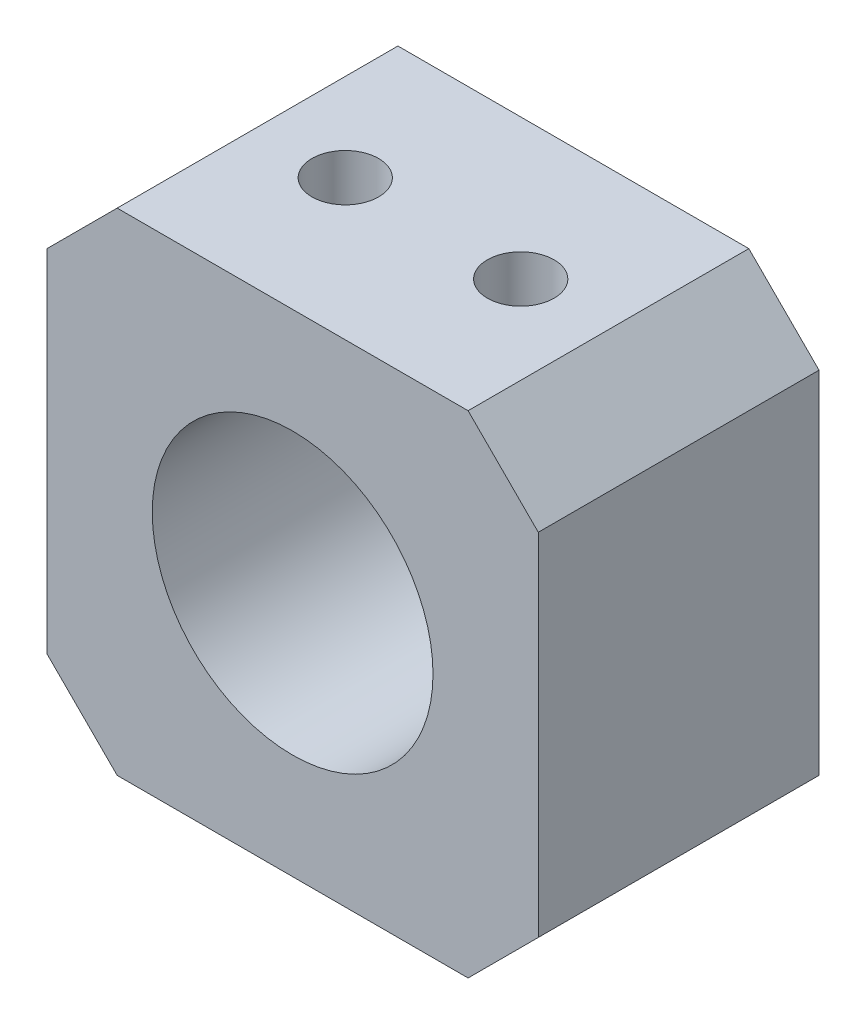
SolidWorks part; units mm, degrees
ref_plane "Piano frontale" through (0, 0, 0) normal (0, 0, 1) x (1, 0, 0)
ref_plane "Piano superiore" through (0, 0, 0) normal (0, 1, 0) x (1, 0, 0)
ref_plane "Piano destro" through (0, 0, 0) normal (1, 0, 0) x (0, 0, -1)
sketch "Schizzo1" plane through (0, 0, 0) normal (0, 0, 1) x (1, 0, 0)
  line L1 (3.5, -3.5) -> (-3.5, -3.5)
  line L2 (3.5, -3.5) -> (3.5, 3.5)
  line L3 (3.5, 3.5) -> (-3.5, 3.5)
  line L4 (-3.5, -3.5) -> (-3.5, 3.5)
  line L5 (3.5, -3.5) -> (-3.5, 3.5) construction
  line L6 (3.5, 3.5) -> (-3.5, -3.5) construction
  circle A0 centre (0, 0) radius 2
  point P0 (0, 0)
  dimension "D3" = 4
  dimension "D1" = 7
  dimension "D2" = 7
extrude "Estrusione-Estrusione1" add sketch "Schizzo1" along normal blind 4
chamfer "Smusso1" distance 1 angle 45 4 edges at (3.5, -3.5, 2) (-3.5, -3.5, 2) (-3.5, 3.5, 2) (3.5, 3.5, 2)
sketch "Schizzo2" plane through (0, 3.5, 0) normal (0, 1, 0) x (1, 0, 0)
  line L0 (0, 0) -> (0, -4) construction
  line L1 (2.5, 0) -> (-2.5, 0) construction
  line L2 (2.5, -4) -> (-2.5, -4) construction
  line L3 (-3.5, -2) -> (3.5, -2) construction
  line L4 (-3.5, -4) -> (-3.5, 0) construction
  line L5 (3.5, 0) -> (3.5, -4) construction
  circle A0 centre (-1.25, -2) radius 0.6
  circle A1 centre (1.25, -2) radius 0.6
  point P16 (0, 0)
  point P17 (0, 0)
  dimension "D1" = 1.2
  dimension "D2" = 1.2
  dimension "D3" = 2.25
  dimension "D4" = 2.5
hole_wizard "Foro filettato M1.2x0.25-1" positions "Schizzo3D1" profile "Schizzo3" tap size "M1.2x0.25" standard "Ansi Metric"
sketch3d "Schizzo3D1"
  point P0 (-1.25, 3.5, 2)
  point P3 (1.25, 3.5, 2)
sketch "Schizzo3" plane through (-1.25, 3.5, 2) normal (1, 0, 0) x (0, 0, 1)
  line L0 (0, 0) -> (0, 1.4854)
  line L1 (0, 1.4854) -> (0.475, 1.2)
  line L2 (0.475, 1.2) -> (0.475, 0)
  line L5 (0.475, 0) -> (0, 0)
  line L10 (0, 1.4854) -> (-0.475, 1.2) construction
  line L11 (0, -6.35) -> (0, 107.95) construction
  dimension "Tap Drill Dia." = 0.95
  dimension "Tap Drill Depth" = 1.2
  dimension "Drill Angle" = 118
cosmetic thread "Filettatura del foro1" parameters "D1"=1, "D2"=1.2
cosmetic thread "Filettatura del foro2" parameters "D1"=1, "D2"=1.2
